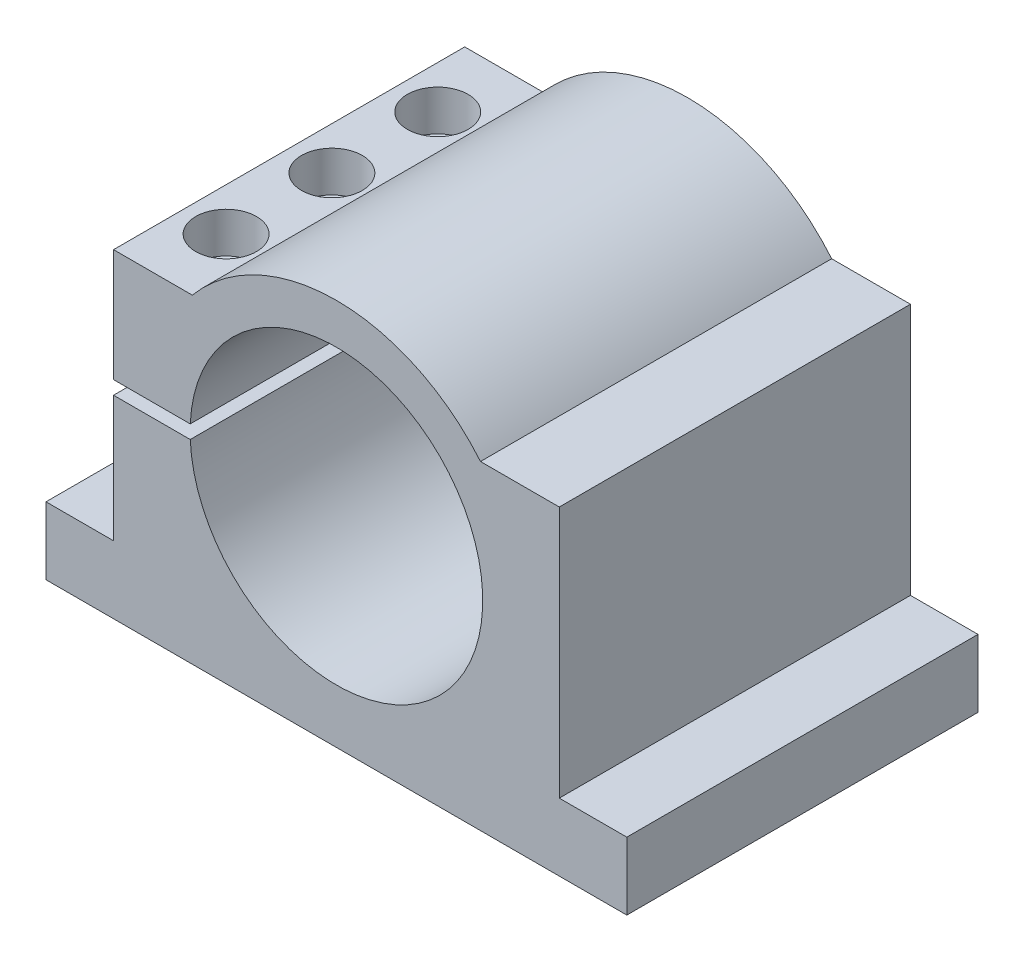
SolidWorks part; units mm, degrees
ref_plane "Спереди" through (0, 0, 0) normal (0, 0, 1) x (1, 0, 0)
ref_plane "Сверху" through (0, 0, 0) normal (0, 1, 0) x (1, 0, 0)
ref_plane "Справа" through (0, 0, 0) normal (1, 0, 0) x (0, 0, -1)
sketch "Эскиз1" plane through (0, 0, 0) normal (0, 0, 1) x (1, 0, 0)
  line L0 (-64.5, 0) -> (64.5, 0)
  line L1 (64.5, 0) -> (64.5, 15)
  line L2 (64.5, 15) -> (49.5, 15)
  line L3 (49.5, 15) -> (49.5, 71)
  line L4 (49.5, 71) -> (32, 71)
  line L5 (-64.5, 0) -> (-64.5, 15)
  line L6 (-64.5, 15) -> (-49.5, 15)
  line L7 (-49.5, 15) -> (-49.5, 43)
  line L8 (-49.5, 71) -> (-32, 71)
  line L9 (-49.5, 43) -> (-32.4654, 43)
  line L10 (-49.5, 46) -> (-32.4654, 46)
  line L11 (-49.5, 46) -> (-49.5, 71)
  arc A0 (-32, 71) -> (32, 71) centre (0, 44.3667) cw
  arc A1 (-32.4654, 43) -> (-32.4654, 46) centre (0, 44.5) ccw
  point P3 (0, 0)
  point P10 (0, 86)
  point P17 (0, 77)
  point P18 (0, 12)
  dimension "D7" = 65
  dimension "D8" = 12
  dimension "D9" = 3
  dimension "D1" = 71
  dimension "D2" = 15
  dimension "D3" = 86
  dimension "D4" = 129
  dimension "D5" = 99
  dimension "D6" = 64
  dimension "D10" = 43
extrude "Бобышка-Вытянуть1" add sketch "Эскиз1" along normal blind 78
sketch "Эскиз2" plane through (0, 71, 0) normal (0, 1, 0) x (1, 0, 0)
  line L0 (-40, -15.5) -> (-40, -62.5) construction
  line L1 (-32, 0) -> (-49.5, 0) construction
  line L2 (-64.5, -78) -> (-64.5, 0) construction
  line L4 (-49.5, -78) -> (-49.5, 0) construction
  circle A0 centre (-40, -39) radius 6.5 construction
  circle A1 centre (-40, -62.5) radius 6.5 construction
  circle A2 centre (-40, -15.5) radius 6.5 construction
  point P7 (-40, -9)
  point P12 (-64.5, -39)
  point P15 (-46.5, -15.5)
  point P16 (-40, -15.5)
  point P17 (-40, -39)
  point P18 (-40, -62.5)
  dimension "D1" = 13
  dimension "D2" = 9
  dimension "D3" = 3
  dimension "D4" = 23.5
ref_plane "Плоскость1" through (-40, 0, 0) normal (-1, 0, 0) x (0, 0, 1)
sketch "Эскиз14" plane through (-40, 0, 0) normal (-1, 0, 0) x (0, 0, 1)
  line L0 (62.5, 71) -> (62.5, 58.1029) construction
  line L1 (69, 71) -> (56, 71) construction
  line L2 (62.5, 58.1029) -> (55.75, 62) construction
  line L3 (55.75, 62) -> (55.75, 71)
  line L4 (78, 71) -> (0, 71) construction
  line L5 (55.75, 71) -> (62.5, 71)
  line L6 (55.75, 62) -> (58.5, 60.4123)
  line L7 (58.5, 60.4123) -> (62.5, 60.4123)
  line L8 (62.5, 71) -> (62.5, 60.4123)
  point P4 (62.5, 64.5514)
  dimension "D1" = 120
  dimension "D2" = 6.75
  dimension "D3" = 9
  dimension "D4" = 4
revolve "Вырез-Повернуть2" cut sketch "Эскиз14" angle 360 about L0
ref_point "Точка1"
ref_point "Точка3"
pattern_linear "Линейный массив1" count 3 spacing 23.5 along (0, 0, -1) of "Вырез-Повернуть2"
hole_wizard "Отверстие обработанное метчиком M8x1.254" positions "Эскиз23" profile "Эскиз24" tap size "M8x1.25" standard "Ansi Metric"
sketch "Эскиз23" plane through (0, 43, 0) normal (0, 1, 0) x (1, 0, 0)
  point P0 (-40, -62.5)
sketch "Эскиз24" plane through (-40, 43, 62.5) normal (1, 0, 0) x (0, 0, 1)
  line L0 (0, 0) -> (0, 27.0429)
  line L1 (0, 27.0429) -> (3.4, 25)
  line L2 (3.4, 25) -> (3.4, 0)
  line L5 (3.4, 0) -> (0, 0)
  line L10 (0, 27.0429) -> (-3.4, 25) construction
  line L11 (0, -6.35) -> (0, 107.95) construction
  dimension "Диаметр сверла" = 6.8
  dimension "Глубина сверла" = 25
  dimension "Угол заточки сверла" = 118
cosmetic thread "Отверстие резьбы6" parameters "D1"=16, "D2"=8
hole_wizard "Диаметр отверстия Ø9.0 (9)2" positions "Эскиз25" profile "Эскиз26" hole size "Ø9.0" standard "Ansi Metric"
sketch "Эскиз25" plane through (0, 46, 0) normal (0, -1, 0) x (-1, 0, 0)
  point P0 (40, -62.5)
sketch "Эскиз26" plane through (-40, 46, 62.5) normal (1, 0, 0) x (0, 0, -1)
  line L0 (0, 0) -> (0, 40)
  line L1 (0, 40) -> (4.5, 40)
  line L2 (4.5, 40) -> (4.5, 0)
  line L5 (4.5, 0) -> (0, 0)
  line L11 (0, -6.35) -> (0, 107.95) construction
  dimension "Диаметр сквозного отверстия" = 9
  dimension "Глубина сквозного отверстия" = 40
ref_point "Точка4"
ref_point "Точка5"
hole_wizard "Отверстие обработанное метчиком M8x1.257" positions "Эскиз35" profile "Эскиз36" tap size "M8x1.25" standard "Ansi Metric"
sketch "Эскиз35" plane through (0, 60.4123, 0) normal (0, 1, 0) x (1, 0, 0)
  point P0 (-40, -39)
sketch "Эскиз36" plane through (-40, 60.4123, 39) normal (1, 0, 0) x (0, 0, 1)
  line L0 (0, 0) -> (0, 14.4123)
  line L1 (0, 14.4123) -> (3.4, 14.4123)
  line L2 (3.4, 14.4123) -> (3.4, 0)
  line L5 (3.4, 0) -> (0, 0)
  line L11 (0, -6.35) -> (0, 107.95) construction
  dimension "Диаметр проходного сверла" = 6.8
  dimension "Глубина проходного сверла" = 14.4123
cosmetic thread "Отверстие резьбы9" parameters "D2"=8
ref_plane "Плоскость2" through (0, 0, 39) normal (0, 0, 1) x (1, 0, 0)
mirror "Зеркальное отражение1" about plane through (0, 0, 39) normal (0, 0, 1) of "Диаметр отверстия Ø9.0 (9)2", "Отверстие обработанное метчиком M8x1.254"
ref_plane "Плоскость3" through (0, 0, 0) normal (-1, 0, 0) x (0, 0, 1)
